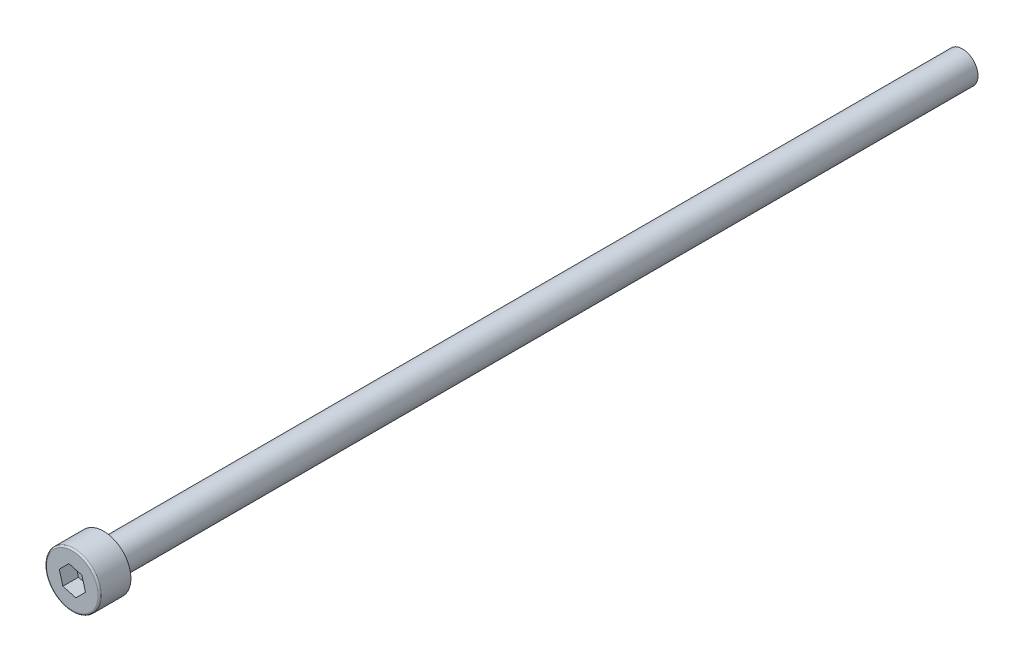
SolidWorks part; units mm, degrees
ref_plane "前视基准面" through (0, 0, 0) normal (0, 0, 1) x (1, 0, 0)
ref_plane "上视基准面" through (0, 0, 0) normal (0, 1, 0) x (1, 0, 0)
ref_plane "右视基准面" through (0, 0, 0) normal (1, 0, 0) x (0, 0, -1)
sketch "草图1" plane through (0, 0, 0) normal (0, 0, 1) x (1, 0, 0)
  circle A0 centre (0, 0) radius 3.5
  dimension "D1" = 7
extrude "凸台-拉伸1" add sketch "草图1" along normal blind 4
sketch "草图2" plane through (0, 0, 4) normal (0, 0, 1) x (1, 0, 0)
  line L1 (-1.2247, -1.2247) -> (0.4483, -1.673)
  line L2 (0.4483, -1.673) -> (1.673, -0.4483)
  line L3 (1.673, -0.4483) -> (1.2247, 1.2247)
  line L4 (1.2247, 1.2247) -> (-0.4483, 1.673)
  line L5 (-0.4483, 1.673) -> (-1.673, 0.4483)
  line L6 (-1.673, 0.4483) -> (-1.2247, -1.2247)
  circle A0 centre (0, 0) radius 1.5 construction
  dimension "D1" = 3
extrude "切除-拉伸1" cut sketch "草图2" against normal blind 2
sketch "草图3" plane through (0, 0, 0) normal (0, 0, -1) x (-1, 0, 0)
  circle A0 centre (0, 0) radius 2
  dimension "D1" = 4
extrude "凸台-拉伸2" add sketch "草图3" along normal blind 110
fillet "圆角1" radius 0.2 1 edges at (3.5, 0, 4)
